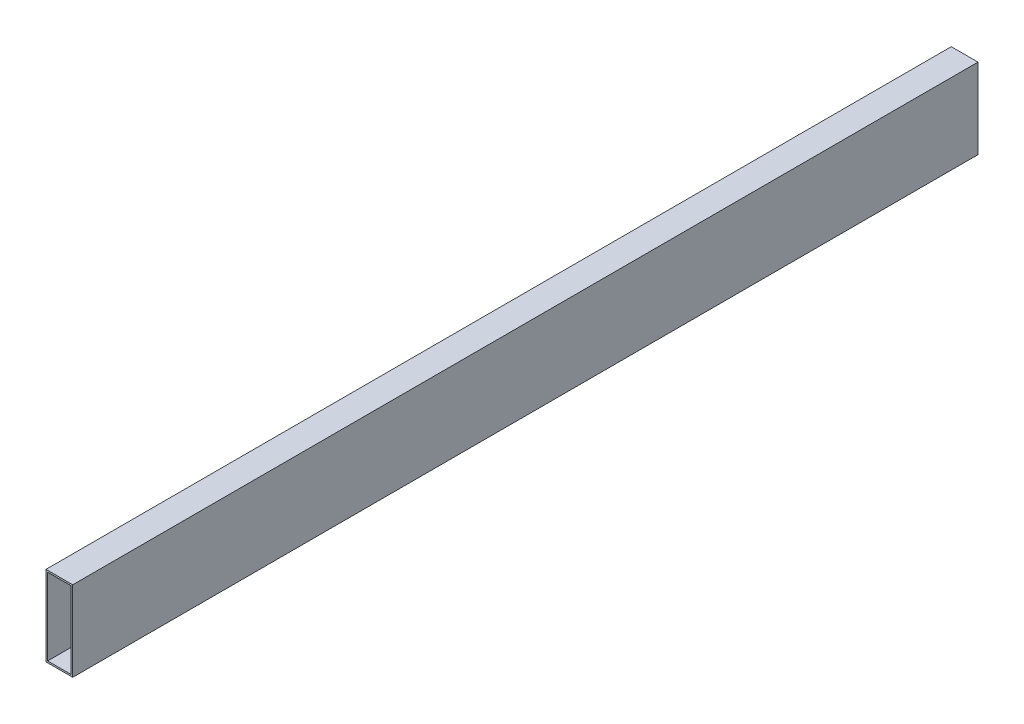
SolidWorks part; units mm, degrees
ref_plane "Front Plane" through (0, 0, 0) normal (0, 0, 1) x (1, 0, 0)
ref_plane "Top Plane" through (0, 0, 0) normal (0, 1, 0) x (1, 0, 0)
ref_plane "Right Plane" through (0, 0, 0) normal (1, 0, 0) x (0, 0, -1)
sketch "Sketch1" plane through (0, 0, 0) normal (0, 0, 1) x (1, 0, 0)
  line L1 (0, 0) -> (50.8, 0)
  line L2 (0, 0) -> (0, 152.4)
  line L3 (0, 152.4) -> (50.8, 152.4)
  line L4 (50.8, 0) -> (50.8, 152.4)
  dimension "D1" = 50.8
  dimension "D2" = 152.4
extrude "Boss-Extrude1" add sketch "Sketch1" along normal blind 1720.85
shell "Shell1" thickness 3.175
